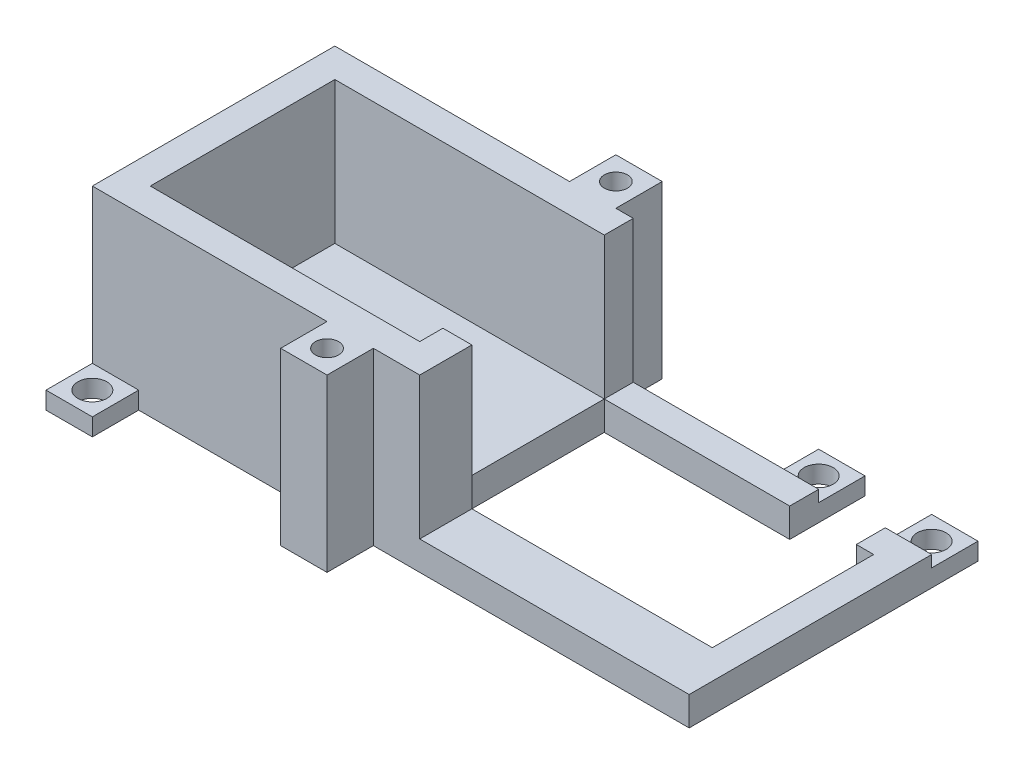
SolidWorks part; units mm, degrees
ref_plane "Front Plane" through (0, 0, 0) normal (0, 0, 1) x (1, 0, 0)
ref_plane "Top Plane" through (0, 0, 0) normal (0, 1, 0) x (1, 0, 0)
ref_plane "Right Plane" through (0, 0, 0) normal (1, 0, 0) x (0, 0, -1)
sketch "Sketch1" plane through (0, 0, 0) normal (0, 1, 0) x (1, 0, 0)
  line L17 (0, 0) -> (51.5, 0)
  line L18 (51.5, 0) -> (51.5, -5)
  line L19 (51.5, -5) -> (5, -5)
  line L20 (5, -5) -> (5, -36.85)
  line L21 (5, -36.85) -> (51.5, -36.85)
  line L22 (51.5, -36.85) -> (51.5, -32.85)
  line L23 (51.5, -32.85) -> (56.5, -32.85)
  line L24 (56.5, -32.85) -> (56.5, -41.85)
  line L25 (56.5, -41.85) -> (0, -41.85)
  line L26 (0, -41.85) -> (0, 0)
  dimension "D1" = 31.85
  dimension "D2" = 5
  dimension "D3" = 5
  dimension "D4" = 5
  dimension "D5" = 5
  dimension "D6" = 51.5
  dimension "D7" = 56.5
  dimension "D8" = 4
extrude "Boss-Extrude1" add sketch "Sketch1" along normal blind 24.5
sketch "Sketch2" plane through (0, 0, 0) normal (0, -1, 0) x (1, 0, 0)
  line L1 (0, 41.85) -> (103, 41.85)
  line L2 (0, 41.85) -> (0, 0)
  line L3 (0, 0) -> (103, 0)
  line L4 (103, 41.85) -> (103, 0)
  dimension "D1" = 103
extrude "Boss-Extrude2" add sketch "Sketch2" along normal blind 5
sketch "Sketch3" plane through (0, 0, 0) normal (0, 1, 0) x (1, 0, 0)
  line L0 (56.5, -32.85) -> (51.5, -32.85) construction
  line L1 (51.5, -5) -> (98, -5)
  line L2 (51.5, -5) -> (51.5, -32.85)
  line L3 (51.5, -32.85) -> (98, -32.85)
  line L4 (98, -5) -> (98, -32.85)
  line L6 (103, 0) -> (103, -41.85) construction
  dimension "D1" = 0
  dimension "D2" = 5
extrude "Cut-Extrude1" cut sketch "Sketch3" against normal blind 26
sketch "Sketch4" plane through (0, 0, 41.85) normal (0, 0, 1) x (1, 0, 0)
  line L1 (0, -5) -> (8, -5)
  line L2 (0, -5) -> (0, -2)
  line L3 (0, -2) -> (8, -2)
  line L4 (8, -5) -> (8, -2)
  dimension "D1" = 3
  dimension "D2" = 8
sketch "Sketch7" plane through (0, 0, 41.85) normal (0, 0, 1) x (1, 0, 0)
  line L1 (0, -2) -> (8, -2)
  line L2 (0, -2) -> (0, -5)
  line L3 (0, -5) -> (8, -5)
  line L4 (8, -2) -> (8, -5)
extrude "Boss-Extrude3" add sketch "Sketch7" along normal blind 8
sketch "Sketch8" plane through (0, -2, 0) normal (0, 1, 0) x (1, 0, 0)
  line L0 (8, -49.85) -> (8, -41.85) construction
  line L1 (0, -41.85) -> (8, -41.85) construction
  circle A0 centre (4, -45.85) radius 2.5
  dimension "D1" = 5
  dimension "D2" = 4
  dimension "D3" = 4
extrude "Cut-Extrude2" cut sketch "Sketch8" against normal blind 8
sketch "Sketch9" plane through (0, 0, 0) normal (0, 0, -1) x (-1, 0, 0)
  line L1 (-103, -5) -> (-95, -5)
  line L2 (-103, -5) -> (-103, -2)
  line L3 (-103, -2) -> (-95, -2)
  line L4 (-95, -5) -> (-95, -2)
  dimension "D1" = 3
  dimension "D2" = 8
extrude "Boss-Extrude4" add sketch "Sketch9" along normal blind 8
sketch "Sketch10" plane through (0, -2, 0) normal (0, 1, 0) x (1, 0, 0)
  line L0 (103, 8) -> (103, 0) construction
  line L1 (95, 8) -> (103, 8) construction
  circle A0 centre (99, 3.9967) radius 2.5
  dimension "D1" = 5
  dimension "D2" = 4
  dimension "D3" = 4.0033
extrude "Cut-Extrude3" cut sketch "Sketch10" against normal blind 8
sketch "Sketch12" plane through (0, 0, 0) normal (0, 1, 0) x (1, 0, 0)
  line L0 (98, -5) -> (51.5, -5) construction
  line L1 (95, -5) -> (83.5, -5)
  line L2 (95, -5) -> (95, 0)
  line L3 (95, 0) -> (83.5, 0)
  line L4 (83.5, -5) -> (83.5, 0)
  line L5 (51.5, 0) -> (103, 0) construction
  line L6 (95, 8) -> (95, 0) construction
  line L7 (51.5, -5) -> (51.5, 0) construction
  dimension "D1" = 0
  dimension "D2" = 32
extrude "Cut-Extrude4" cut sketch "Sketch12" against normal blind 8
sketch "Sketch14" plane through (0, 0, 0) normal (0, 0, -1) x (-1, 0, 0)
  line L1 (-83.5, -5) -> (-75.5, -5)
  line L2 (-83.5, -5) -> (-83.5, -2)
  line L3 (-83.5, -2) -> (-75.5, -2)
  line L4 (-75.5, -5) -> (-75.5, -2)
  dimension "D1" = 8
  dimension "D2" = 3
extrude "Boss-Extrude5" add sketch "Sketch14" along normal blind 8
sketch "Sketch15" plane through (0, -2, 0) normal (0, 1, 0) x (1, 0, 0)
  line L0 (75.5, 8) -> (83.5, 8) construction
  line L1 (83.5, 8) -> (83.5, 0) construction
  circle A0 centre (79.5, 4) radius 2.5
  dimension "D1" = 5
  dimension "D2" = 4
  dimension "D3" = 4
extrude "Cut-Extrude5" cut sketch "Sketch15" against normal blind 8
sketch "Sketch16" plane through (0, 0, 0) normal (0, 0, -1) x (-1, 0, 0)
  line L12 (-51.5, 24.5) -> (0, 24.5) construction
  line L17 (-48.5, 24.5) -> (-40.5, 24.5)
  line L18 (-48.5, 24.5) -> (-48.5, -5)
  line L19 (-48.5, -5) -> (-40.5, -5)
  line L20 (-40.5, 24.5) -> (-40.5, -5)
  line L21 (0, -5) -> (-75.5, -5) construction
  line L22 (-51.5, 24.5) -> (-51.5, 0) construction
  dimension "D1" = 8
  dimension "D2" = 3
extrude "Boss-Extrude6" add sketch "Sketch16" along normal blind 8
sketch "Sketch17" plane through (0, 0, 41.85) normal (0, 0, 1) x (1, 0, 0)
  line L0 (0, 24.5) -> (56.5, 24.5) construction
  line L1 (48.5, 24.5) -> (40.5, 24.5)
  line L2 (48.5, 24.5) -> (48.5, -5)
  line L3 (48.5, -5) -> (40.5, -5)
  line L4 (40.5, 24.5) -> (40.5, -5)
  line L5 (103, -5) -> (8, -5) construction
  line L6 (56.5, 24.5) -> (56.5, 0) construction
  dimension "D1" = 8
  dimension "D2" = 8
extrude "Boss-Extrude7" add sketch "Sketch17" along normal blind 8
sketch "Sketch18" plane through (0, 24.5, 0) normal (0, 1, 0) x (1, 0, 0)
  line L0 (48.5, 8) -> (48.5, 0) construction
  line L2 (40.5, 8) -> (48.5, 8) construction
  line L3 (48.5, -49.85) -> (48.5, -41.85) construction
  line L4 (48.5, -49.85) -> (40.5, -49.85) construction
  circle A0 centre (44.5, 4) radius 2
  circle A1 centre (44.5, -45.85) radius 2
  dimension "D5" = 4
  dimension "D6" = 4
  dimension "D1" = 4
  dimension "D2" = 4
  dimension "D3" = 4
  dimension "D4" = 4
extrude "Cut-Extrude6" cut sketch "Sketch18" against normal blind 10
